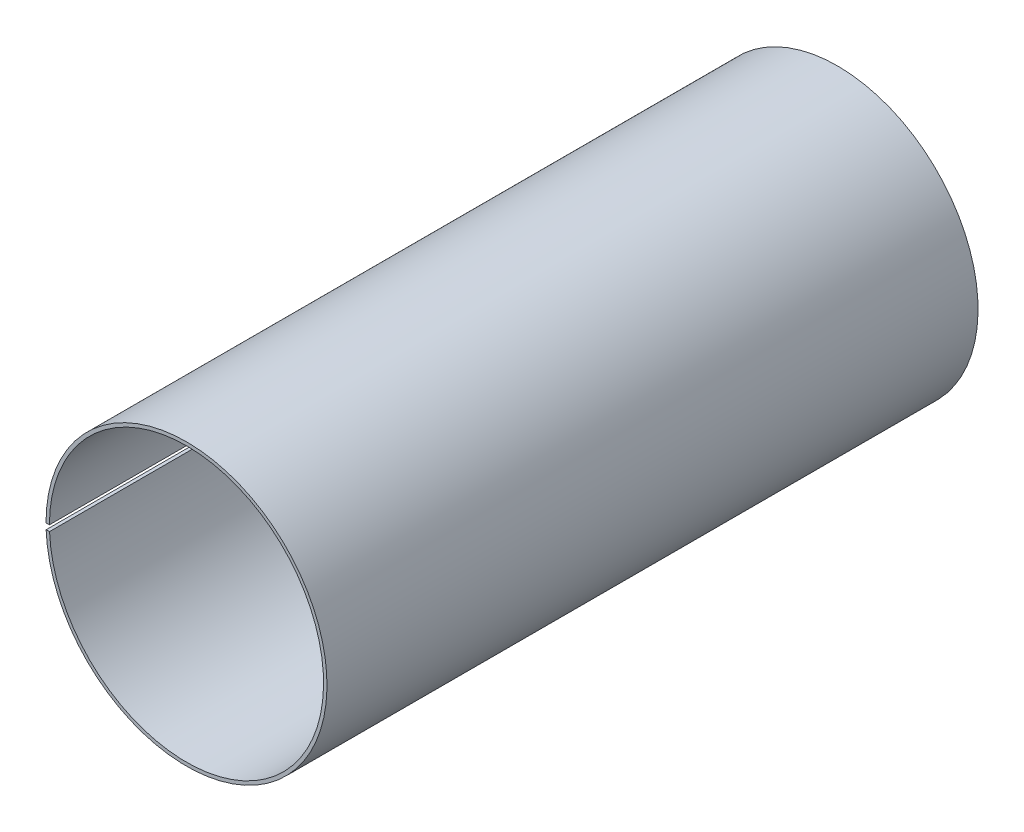
SolidWorks part; units mm, degrees
ref_plane "Front Plane" through (0, 0, 0) normal (0, 0, 1) x (1, 0, 0)
ref_plane "Top Plane" through (0, 0, 0) normal (0, 1, 0) x (1, 0, 0)
ref_plane "Right Plane" through (0, 0, 0) normal (1, 0, 0) x (0, 0, -1)
sketch "Sketch1" plane through (0, 0, 0) normal (0, 0, 1) x (1, 0, 0)
  line L0 (-410, 0) -> (-400, 0)
  line L2 (-409.6405, -17.1654) -> (-399.6493, -16.7467)
  arc A0 (-399.6493, -16.7467) -> (-400, 0) centre (0, 0) ccw
  arc A1 (-409.6405, -17.1654) -> (-410, 0) centre (0, 0) ccw
  circle A2 centre (0, 0) radius 410 construction
  circle A3 centre (0, 0) radius 400 construction
  dimension "D1" = 800
  dimension "D3" = 9.9912
  dimension "D2" = 10
extrude "Boss-Extrude1" add sketch "Sketch1" along normal blind 1900
